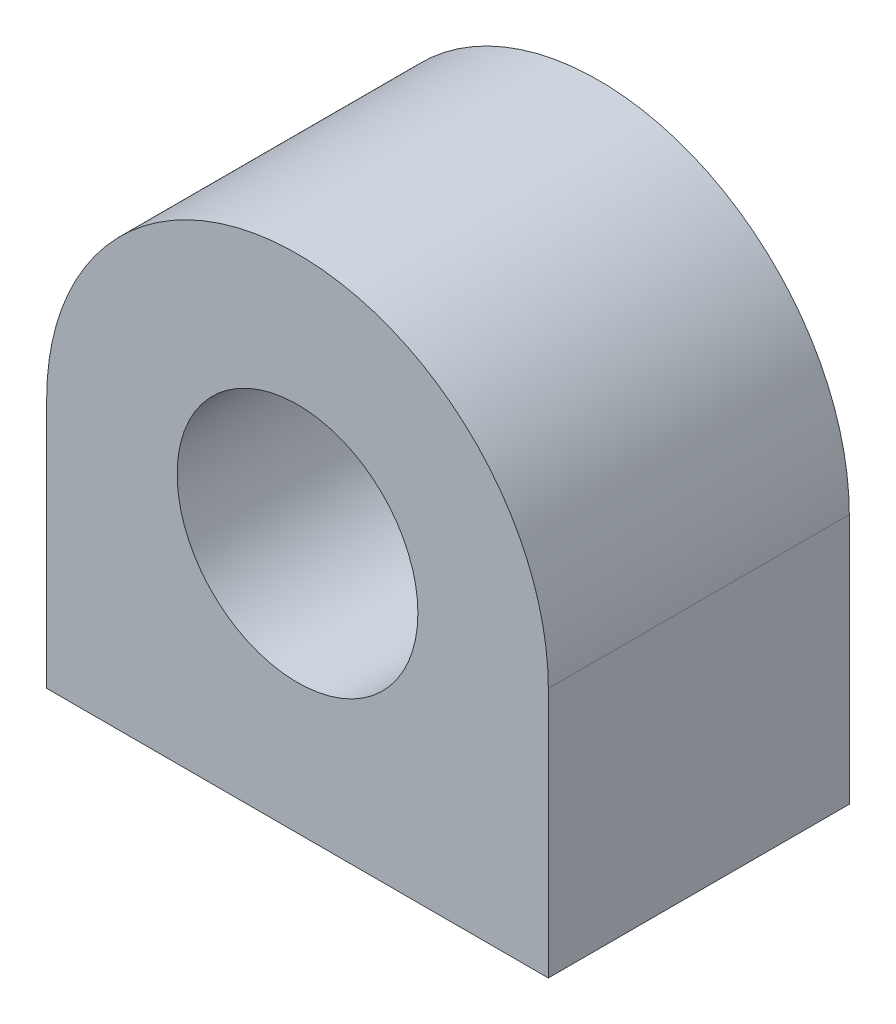
SolidWorks part; units mm, degrees
ref_plane "前视基准面" through (0, 0, 0) normal (0, 0, 1) x (1, 0, 0)
ref_plane "上视基准面" through (0, 0, 0) normal (0, 1, 0) x (1, 0, 0)
ref_plane "右视基准面" through (0, 0, 0) normal (1, 0, 0) x (0, 0, -1)
other "Configuration Table"
sketch "草图1" plane through (0, 0, 0) normal (0, 0, 1) x (1, 0, 0)
  line L2 (-25, 0) -> (-25, -25)
  line L3 (-25, -25) -> (25, -25)
  line L4 (25, 0) -> (25, -25)
  circle A0 centre (0, 0) radius 12
  arc A1 (25, 0) -> (-25, 0) centre (0, 0) ccw
  dimension "D1" = 24
  dimension "D2" = 50
extrude "凸台-拉伸1" add sketch "草图1" along normal blind 30
